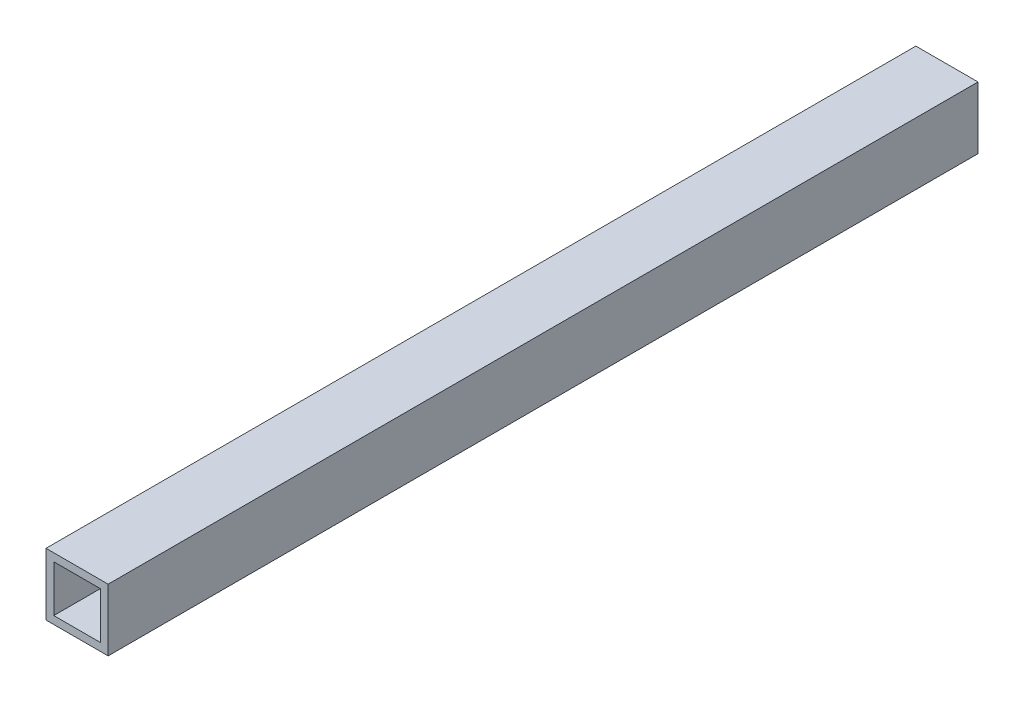
SolidWorks part; units mm, degrees
material "6061 Alloy"
ref_plane "Front Plane" through (0, 0, 0) normal (0, 0, 1) x (1, 0, 0)
ref_plane "Top Plane" through (0, 0, 0) normal (0, 1, 0) x (1, 0, 0)
ref_plane "Right Plane" through (0, 0, 0) normal (1, 0, 0) x (0, 0, -1)
sketch "Sketch1" plane through (0, 0, 0) normal (0, 0, 1) x (1, 0, 0)
  line L0 (12.7, 0) -> (9.525, 0) construction
  line L1 (-12.7, 0) -> (12.7, 0) construction
  line L2 (0, 12.7) -> (0, -12.7)
  point P7 (0, 0)
sketch "Sketch2" plane through (0, 0, 0) normal (1, 0, 0) x (0, 0, -1)
  line L0 (177.8, 0) -> (-177.8, 0)
  point P4 (0, 0)
  dimension "Length" = 355.6
sketch "Sketch3" plane through (0, 0, 0) normal (0, 0, 1) x (1, 0, 0)
  line L0 (-12.7, 0) -> (12.7, 0) construction
  line L5 (12.7, -12.7) -> (-12.7, -12.7)
  line L6 (12.7, -12.7) -> (12.7, 12.7)
  line L11 (12.7, 12.7) -> (-12.7, 12.7)
  line L12 (-12.7, -12.7) -> (-12.7, 12.7)
  line L14 (12.7, -12.7) -> (-12.7, 12.7) construction
  line L15 (12.7, 12.7) -> (-12.7, -12.7) construction
  line L16 (9.525, -9.525) -> (-9.525, -9.525)
  line L17 (9.525, -9.525) -> (9.525, 9.525)
  line L18 (9.525, 9.525) -> (-9.525, 9.525)
  line L19 (-9.525, -9.525) -> (-9.525, 9.525)
  line L20 (9.525, -9.525) -> (-9.525, 9.525) construction
  line L21 (9.525, 9.525) -> (-9.525, -9.525) construction
  point P0 (0, 0)
  point P5 (0, 0)
  point P13 (9.525, -12.7)
  dimension "D1" = 3.175
  dimension "D3" = 25.4
  dimension "D4" = 25.4
extrude "Boss-Extrude1" add sketch "Sketch3" along normal up to vertex (177.8 mm away) and the other way up to vertex (177.8 mm away) up to point (0, 0, 177.8) other way up to point (0, 0, -177.8)
sketch "Sketch5" plane through (0, 0, 0) normal (1, 0, 0) x (0, 0, -1)
  line L0 (-177.8, 0) -> (177.8, 0) construction
  line L3 (-177.8, -12.7) -> (-177.8, 12.7) construction
  line L4 (177.8, -12.7) -> (177.8, 12.7) construction
  point P6 (-149.225, 0)
  point P7 (-139.7, 0)
  point P8 (139.7, 0)
  point P10 (149.225, 0)
  dimension "D1" = 28.575
  dimension "D2" = 38.1
  dimension "D3" = 28.575
  dimension "D4" = 38.1
equation "\"D1@Sketch3\"=\"Wall thickness@Sketch1\""
equation "\"D1@Sketch5\"=\"Width@Sketch1\"*1.125"
equation "\"D2@Sketch5\"=\"Width@Sketch1\"*1.5"
equation "\"D3@Sketch5\"=\"D1@Sketch5\""
equation "\"D4@Sketch5\"=\"D2@Sketch5\""
equation "\"D2@Sketch3\"=\"Wall Thickness@Sketch1\""
